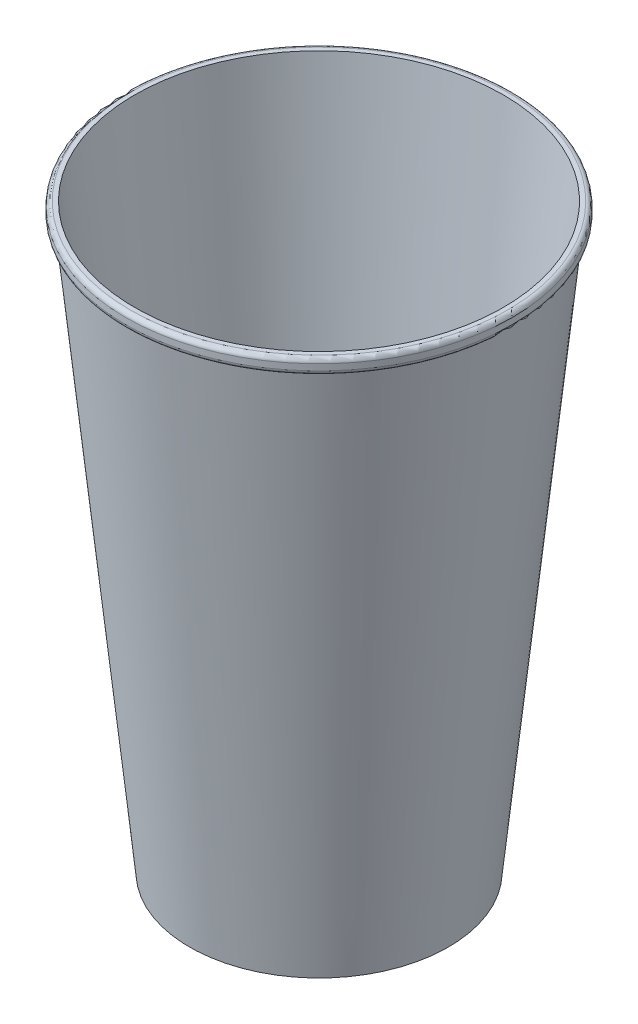
SolidWorks part; units mm, degrees
ref_plane "Alzado" through (0, 0, 0) normal (0, 0, 1) x (1, 0, 0)
ref_plane "Planta" through (0, 0, 0) normal (0, 1, 0) x (1, 0, 0)
ref_plane "Vista lateral" through (0, 0, 0) normal (1, 0, 0) x (0, 0, -1)
sketch "Croquis1" plane through (0, 0, 0) normal (0, 0, 1) x (1, 0, 0)
  line L0 (29.5052, 0) -> (42.6588, 129.1)
  line L1 (29.5052, 0) -> (28.5, 0)
  line L2 (28.5, 0) -> (29.1623, 6.5)
  line L3 (0, 0) -> (0, 7.5) construction
  line L4 (29.1623, 6.5) -> (0, 6.5)
  line L5 (0, 7.5) -> (29.2642, 7.5)
  line L6 (29.2642, 7.5) -> (42, 132.5)
  line L7 (42, 132.5) -> (44, 132.5)
  line L8 (42.6588, 129.1) -> (44, 129.1)
  line L9 (44, 129.1) -> (44, 132.5)
  line L10 (0, 7.5) -> (0, 6.5)
  line L11 (0, 7.5) -> (0, 70) construction
  line L12 (0, 70) -> (36.6373, 70) construction
  dimension "D4" = 42
  dimension "D1" = 28.5
  dimension "D2" = 1
  dimension "D3" = 6.5
  dimension "D5" = 44
  dimension "D6" = 3.4
  dimension "D7" = 125
  dimension "D8" = 1
  dimension "D9" = 70
  dimension "D10" = 36.6373
revolve "Revolución1" add sketch "Croquis1" angle 360 about L3
fillet "Redondeo1" radius 1 2 edges at (0, 129.1, -44) (0, 132.5, -44)
